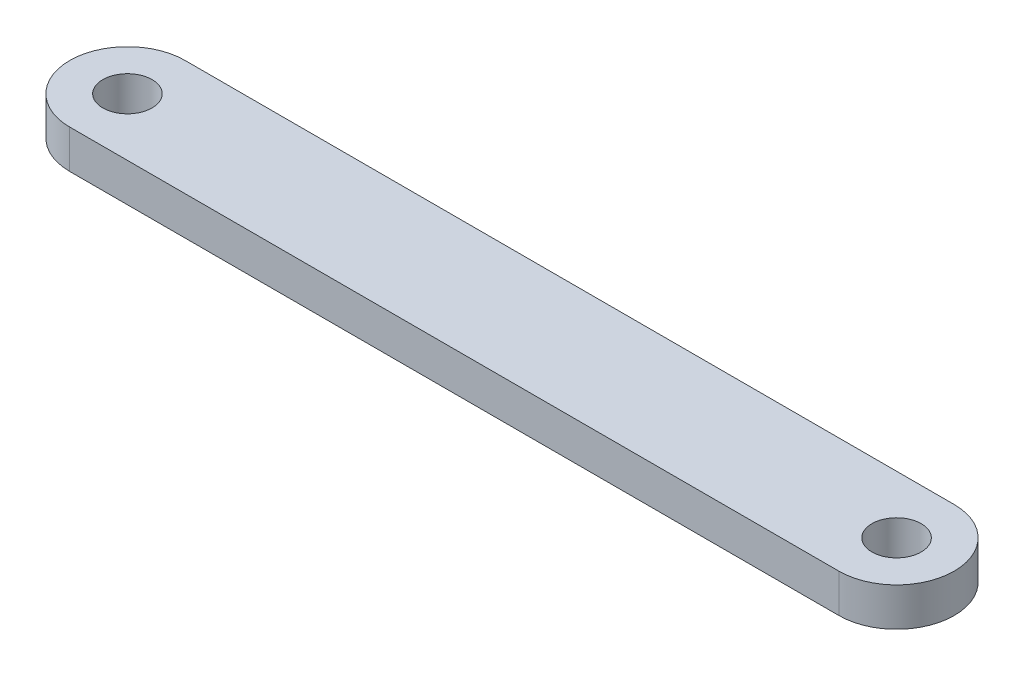
SolidWorks part; units mm, degrees
ref_plane "Front Plane" through (0, 0, 0) normal (0, 0, 1) x (1, 0, 0)
ref_plane "Top Plane" through (0, 0, 0) normal (0, 1, 0) x (1, 0, 0)
ref_plane "Right Plane" through (0, 0, 0) normal (1, 0, 0) x (0, 0, -1)
sketch "Sketch1" plane through (0, 0, 0) normal (0, 1, 0) x (1, 0, 0)
  line L0 (0, 0) -> (-63.5, 0) construction
  line L1 (0, -4.7625) -> (-63.5, -4.7625)
  line L2 (0, 4.7625) -> (-63.5, 4.7625)
  arc A0 (0, -4.7625) -> (0, 4.7625) centre (0, 0) ccw
  arc A1 (-63.5, 4.7625) -> (-63.5, -4.7625) centre (-63.5, 0) ccw
  circle A2 centre (-63.5, 0) radius 2.032
  circle A3 centre (0, 0) radius 2.032
  point P3 (-31.75, 0)
  dimension "D1" = 4.7625
  dimension "D3" = 4.064
  dimension "D2" = 63.5
extrude "Boss-Extrude1" add sketch "Sketch1" along normal blind 3.175
